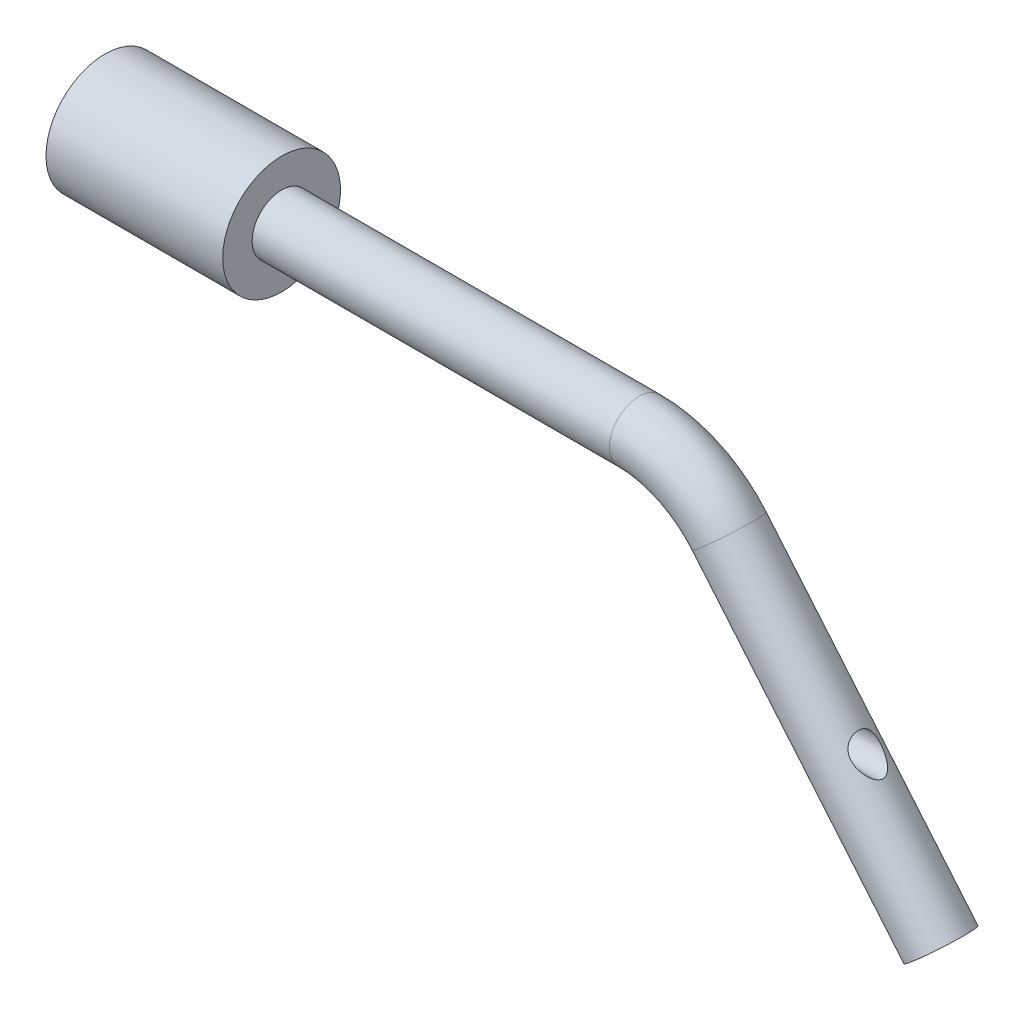
SolidWorks part; units mm, degrees
ref_plane "Přední rovina" through (0, 0, 0) normal (0, 0, 1) x (1, 0, 0)
ref_plane "Horní rovina" through (0, 0, 0) normal (0, 1, 0) x (1, 0, 0)
ref_plane "Pravá rovina" through (0, 0, 0) normal (1, 0, 0) x (0, 0, -1)
sketch "Draha" plane through (0, 0, 0) normal (0, 0, 1) x (1, 0, 0)
  line L0 (0, 0) -> (90.6738, 0)
  line L1 (105.9947, -7.1442) -> (141.955, -50)
  arc A0 (90.6738, 0) -> (105.9947, -7.1442) centre (90.6738, -20) cw
  point P6 (100, 0)
  dimension "D4" = 20
  dimension "D1" = 100
  dimension "D2" = 50
  dimension "D3" = 50
sketch "Prurez" plane through (0, 0, 0) normal (1, 0, 0) x (0, 0, -1)
  circle A0 centre (0, 0) radius 5
  dimension "D1" = 10
sweep "Táhnout po křivce1" add profiles "Prurez" path "Draha"
sketch "Skica3" plane through (0, 0, 0) normal (-1, 0, 0) x (0, 0, 1)
  circle A0 centre (0, 0) radius 10
  dimension "D1" = 20
extrude "Přidat vysunutím1" add sketch "Skica3" against normal blind 30
sketch "Skica4" plane through (0, 0, 0) normal (-1, 0, 0) x (0, 0, 1)
  line L0 (0, 0) -> (0, -28) construction
  circle A0 centre (0, -28) radius 2.5
  dimension "D1" = 5
  dimension "D2" = 28
extrude "Odebrat vysunutím1" cut sketch "Skica4" against normal through all
